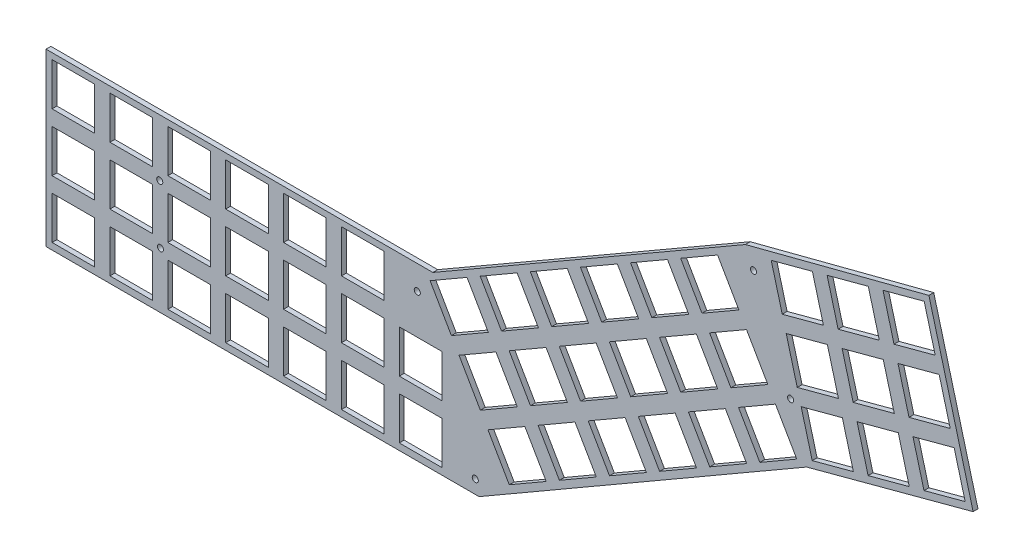
SolidWorks part; units mm, degrees
ref_plane "Plan de face" through (0, 0, 0) normal (0, 0, 1) x (1, 0, 0)
ref_plane "Plan de dessus" through (0, 0, 0) normal (0, 1, 0) x (1, 0, 0)
ref_plane "Plan de droite" through (0, 0, 0) normal (1, 0, 0) x (0, 0, -1)
sketch "Model" plane through (0, 0, 0) normal (0, 0, 1) x (1, 0, 0)
  line L0 (-149.6088, -15.6876) -> (-135.6088, -15.6876) construction
  line L1 (-149.6088, 3.3124) -> (-135.6088, 3.3124) construction
  line L2 (-149.6088, 3.3124) -> (-149.6088, -10.6876) construction
  line L3 (-149.6088, -10.6876) -> (-135.6088, -10.6876) construction
  line L4 (-135.6088, 3.3124) -> (-135.6088, -10.6876) construction
  line L5 (-149.6088, -15.6876) -> (-149.6088, -29.6876) construction
  line L6 (-149.6088, -29.6876) -> (-135.6088, -29.6876) construction
  line L7 (-135.6088, -15.6876) -> (-135.6088, -29.6876) construction
  line L8 (-149.6088, -34.6876) -> (-135.6088, -34.6876) construction
  line L9 (-149.6088, -34.6876) -> (-149.6088, -48.6876) construction
  line L10 (-149.6088, -48.6876) -> (-135.6088, -48.6876) construction
  line L11 (-135.6088, -34.6876) -> (-135.6088, -48.6876) construction
  line L12 (-149.6088, 3.3124) -> (-149.6088, -15.6876) construction
  line L13 (-130.6088, -15.6876) -> (-116.6088, -15.6876) construction
  line L14 (-130.6088, 3.3124) -> (-116.6088, 3.3124) construction
  line L15 (-130.6088, 3.3124) -> (-130.6088, -10.6876) construction
  line L16 (-130.6088, -10.6876) -> (-116.6088, -10.6876) construction
  line L17 (-116.6088, 3.3124) -> (-116.6088, -10.6876) construction
  line L18 (-130.6088, -15.6876) -> (-130.6088, -29.6876) construction
  line L19 (-130.6088, -29.6876) -> (-116.6088, -29.6876) construction
  line L20 (-116.6088, -15.6876) -> (-116.6088, -29.6876) construction
  line L21 (-130.6088, -34.6876) -> (-116.6088, -34.6876) construction
  line L22 (-130.6088, -34.6876) -> (-130.6088, -48.6876) construction
  line L23 (-130.6088, -48.6876) -> (-116.6088, -48.6876) construction
  line L24 (-116.6088, -34.6876) -> (-116.6088, -48.6876) construction
  line L25 (-130.6088, 3.3124) -> (-130.6088, -15.6876) construction
  line L26 (-111.6088, -15.6876) -> (-97.6088, -15.6876) construction
  line L27 (-111.6088, 3.3124) -> (-97.6088, 3.3124) construction
  line L28 (-111.6088, 3.3124) -> (-111.6088, -10.6876) construction
  line L29 (-111.6088, -10.6876) -> (-97.6088, -10.6876) construction
  line L30 (-97.6088, 3.3124) -> (-97.6088, -10.6876) construction
  line L31 (-111.6088, -15.6876) -> (-111.6088, -29.6876) construction
  line L32 (-111.6088, -29.6876) -> (-97.6088, -29.6876) construction
  line L33 (-97.6088, -15.6876) -> (-97.6088, -29.6876) construction
  line L34 (-111.6088, -34.6876) -> (-97.6088, -34.6876) construction
  line L35 (-111.6088, -34.6876) -> (-111.6088, -48.6876) construction
  line L36 (-111.6088, -48.6876) -> (-97.6088, -48.6876) construction
  line L37 (-97.6088, -34.6876) -> (-97.6088, -48.6876) construction
  line L38 (-111.6088, 3.3124) -> (-111.6088, -15.6876) construction
  line L39 (-92.6088, -15.6876) -> (-78.6088, -15.6876) construction
  line L40 (-92.6088, 3.3124) -> (-78.6088, 3.3124) construction
  line L41 (-92.6088, 3.3124) -> (-92.6088, -10.6876) construction
  line L42 (-92.6088, -10.6876) -> (-78.6088, -10.6876) construction
  line L43 (-78.6088, 3.3124) -> (-78.6088, -10.6876) construction
  line L44 (-92.6088, -15.6876) -> (-92.6088, -29.6876) construction
  line L45 (-92.6088, -29.6876) -> (-78.6088, -29.6876) construction
  line L46 (-78.6088, -15.6876) -> (-78.6088, -29.6876) construction
  line L47 (-92.6088, -34.6876) -> (-78.6088, -34.6876) construction
  line L48 (-92.6088, -34.6876) -> (-92.6088, -48.6876) construction
  line L49 (-92.6088, -48.6876) -> (-78.6088, -48.6876) construction
  line L50 (-78.6088, -34.6876) -> (-78.6088, -48.6876) construction
  line L51 (-92.6088, 3.3124) -> (-92.6088, -15.6876) construction
  line L52 (-73.6088, -15.6876) -> (-59.6088, -15.6876) construction
  line L53 (-73.6088, 3.3124) -> (-59.6088, 3.3124) construction
  line L54 (-73.6088, 3.3124) -> (-73.6088, -10.6876) construction
  line L55 (-73.6088, -10.6876) -> (-59.6088, -10.6876) construction
  line L56 (-59.6088, 3.3124) -> (-59.6088, -10.6876) construction
  line L57 (-73.6088, -15.6876) -> (-73.6088, -29.6876) construction
  line L58 (-73.6088, -29.6876) -> (-59.6088, -29.6876) construction
  line L59 (-59.6088, -15.6876) -> (-59.6088, -29.6876) construction
  line L60 (-73.6088, -34.6876) -> (-59.6088, -34.6876) construction
  line L61 (-73.6088, -34.6876) -> (-73.6088, -48.6876) construction
  line L62 (-73.6088, -48.6876) -> (-59.6088, -48.6876) construction
  line L63 (-59.6088, -34.6876) -> (-59.6088, -48.6876) construction
  line L64 (-73.6088, 3.3124) -> (-73.6088, -15.6876) construction
  line L65 (-54.6088, -15.6876) -> (-40.6088, -15.6876) construction
  line L66 (-54.6088, 3.3124) -> (-40.6088, 3.3124) construction
  line L67 (-54.6088, 3.3124) -> (-54.6088, -10.6876) construction
  line L68 (-54.6088, -10.6876) -> (-40.6088, -10.6876) construction
  line L69 (-40.6088, 3.3124) -> (-40.6088, -10.6876) construction
  line L70 (-54.6088, -15.6876) -> (-54.6088, -29.6876) construction
  line L71 (-54.6088, -29.6876) -> (-40.6088, -29.6876) construction
  line L72 (-40.6088, -15.6876) -> (-40.6088, -29.6876) construction
  line L73 (-54.6088, -34.6876) -> (-40.6088, -34.6876) construction
  line L74 (-54.6088, -34.6876) -> (-54.6088, -48.6876) construction
  line L75 (-54.6088, -48.6876) -> (-40.6088, -48.6876) construction
  line L76 (-40.6088, -34.6876) -> (-40.6088, -48.6876) construction
  line L77 (-54.6088, 3.3124) -> (-54.6088, -15.6876) construction
  line L78 (-35.6088, -15.6876) -> (-21.6088, -15.6876) construction
  line L79 (-35.6088, 3.3124) -> (-21.6088, 3.3124) construction
  line L80 (-35.6088, 3.3124) -> (-35.6088, -10.6876) construction
  line L81 (-35.6088, -10.6876) -> (-21.6088, -10.6876) construction
  line L82 (-21.6088, 3.3124) -> (-21.6088, -10.6876) construction
  line L83 (-35.6088, -15.6876) -> (-35.6088, -29.6876) construction
  line L84 (-35.6088, -29.6876) -> (-21.6088, -29.6876) construction
  line L85 (-21.6088, -15.6876) -> (-21.6088, -29.6876) construction
  line L86 (-35.6088, -34.6876) -> (-21.6088, -34.6876) construction
  line L87 (-35.6088, -34.6876) -> (-35.6088, -48.6876) construction
  line L88 (-35.6088, -48.6876) -> (-21.6088, -48.6876) construction
  line L89 (-21.6088, -34.6876) -> (-21.6088, -48.6876) construction
  line L90 (-35.6088, 3.3124) -> (-35.6088, -15.6876) construction
  line L91 (-149.6088, -15.6876) -> (-130.6088, -15.6876) construction
  line L92 (-19.6088, -13.6876) -> (-18.8669, -14.9725) construction
  line L93 (-37.6088, 5.3124) -> (-19.6088, 5.3124) construction
  line L94 (-19.6088, 5.3124) -> (-19.6088, -12.6876) construction
  line L95 (-37.6088, -12.6876) -> (-19.6088, -12.6876) construction
  line L96 (-37.6088, 5.3124) -> (-37.6088, -12.6876) construction
  line L97 (-56.6088, 5.3124) -> (-38.6088, 5.3124) construction
  line L98 (-38.6088, 5.3124) -> (-38.6088, -12.6876) construction
  line L99 (-56.6088, -12.6876) -> (-38.6088, -12.6876) construction
  line L100 (-56.6088, 5.3124) -> (-56.6088, -12.6876) construction
  line L101 (3.8161, 21.7392) -> (12.8161, 6.1508) construction
  line L102 (12.8161, 6.1508) -> (-2.7723, -2.8492) construction
  line L103 (-11.7723, 12.7392) -> (-2.7723, -2.8492) construction
  line L104 (3.8161, 21.7392) -> (-11.7723, 12.7392) construction
  line L105 (-12.6383, 12.2392) -> (-3.6383, -3.3492) construction
  line L106 (-3.6383, -3.3492) -> (-19.2268, -12.3492) construction
  line L107 (-28.2268, 3.2392) -> (-19.2268, -12.3492) construction
  line L108 (-12.6383, 12.2392) -> (-28.2268, 3.2392) construction
  line L109 (88.6341, 26.8303) -> (73.0456, 17.8303) construction
  line L110 (-13.3704, 9.5072) -> (-3.8704, -6.9473) construction
  line L111 (3.0841, 19.0072) -> (12.5841, 2.5527) construction
  line L112 (19.5386, 28.5072) -> (29.0386, 12.0527) construction
  line L113 (35.9931, 38.0072) -> (45.4931, 21.5527) construction
  line L114 (52.4475, 47.5072) -> (61.9475, 31.0527) construction
  line L115 (68.902, 57.0072) -> (78.402, 40.5527) construction
  line L116 (73.0456, 17.8303) -> (82.0456, 2.2418) construction
  line L117 (-6.4947, -30.4018) -> (0.5053, -42.5261) construction
  line L118 (12.6296, -35.5261) -> (0.5053, -42.5261) construction
  line L119 (5.6296, -23.4018) -> (12.6296, -35.5261) construction
  line L120 (5.6296, -23.4018) -> (-6.4947, -30.4018) construction
  line L121 (-15.9947, -13.9473) -> (-8.9947, -26.0717) construction
  line L122 (3.1296, -19.0717) -> (-8.9947, -26.0717) construction
  line L123 (-3.8704, -6.9473) -> (3.1296, -19.0717) construction
  line L124 (-25.4947, 2.5072) -> (-18.4947, -9.6172) construction
  line L125 (-6.3704, -2.6172) -> (-18.4947, -9.6172) construction
  line L126 (-13.3704, 9.5072) -> (-6.3704, -2.6172) construction
  line L127 (-13.3704, 9.5072) -> (-25.4947, 2.5072) construction
  line L128 (-3.8704, -6.9473) -> (-15.9947, -13.9473) construction
  line L129 (9.9597, -20.9018) -> (16.9597, -33.0261) construction
  line L130 (29.0841, -26.0261) -> (16.9597, -33.0261) construction
  line L131 (22.0841, -13.9018) -> (29.0841, -26.0261) construction
  line L132 (22.0841, -13.9018) -> (9.9597, -20.9018) construction
  line L133 (0.4597, -4.4473) -> (7.4597, -16.5717) construction
  line L134 (19.5841, -9.5717) -> (7.4597, -16.5717) construction
  line L135 (12.5841, 2.5527) -> (19.5841, -9.5717) construction
  line L136 (-9.0403, 12.0072) -> (-2.0403, -0.1172) construction
  line L137 (10.0841, 6.8828) -> (-2.0403, -0.1172) construction
  line L138 (3.0841, 19.0072) -> (10.0841, 6.8828) construction
  line L139 (3.0841, 19.0072) -> (-9.0403, 12.0072) construction
  line L140 (12.5841, 2.5527) -> (0.4597, -4.4473) construction
  line L141 (26.4142, -11.4018) -> (33.4142, -23.5261) construction
  line L142 (45.5386, -16.5261) -> (33.4142, -23.5261) construction
  line L143 (38.5386, -4.4018) -> (45.5386, -16.5261) construction
  line L144 (38.5386, -4.4018) -> (26.4142, -11.4018) construction
  line L145 (16.9142, 5.0527) -> (23.9142, -7.0717) construction
  line L146 (36.0386, -0.0717) -> (23.9142, -7.0717) construction
  line L147 (29.0386, 12.0527) -> (36.0386, -0.0717) construction
  line L148 (7.4142, 21.5072) -> (14.4142, 9.3828) construction
  line L149 (26.5386, 16.3828) -> (14.4142, 9.3828) construction
  line L150 (19.5386, 28.5072) -> (26.5386, 16.3828) construction
  line L151 (19.5386, 28.5072) -> (7.4142, 21.5072) construction
  line L152 (29.0386, 12.0527) -> (16.9142, 5.0527) construction
  line L153 (42.8687, -1.9018) -> (49.8687, -14.0261) construction
  line L154 (61.9931, -7.0261) -> (49.8687, -14.0261) construction
  line L155 (54.9931, 5.0982) -> (61.9931, -7.0261) construction
  line L156 (54.9931, 5.0982) -> (42.8687, -1.9018) construction
  line L157 (33.3687, 14.5527) -> (40.3687, 2.4283) construction
  line L158 (52.4931, 9.4283) -> (40.3687, 2.4283) construction
  line L159 (45.4931, 21.5527) -> (52.4931, 9.4283) construction
  line L160 (23.8687, 31.0072) -> (30.8687, 18.8828) construction
  line L161 (42.9931, 25.8828) -> (30.8687, 18.8828) construction
  line L162 (35.9931, 38.0072) -> (42.9931, 25.8828) construction
  line L163 (35.9931, 38.0072) -> (23.8687, 31.0072) construction
  line L164 (45.4931, 21.5527) -> (33.3687, 14.5527) construction
  line L165 (59.3232, 7.5982) -> (66.3232, -4.5261) construction
  line L166 (78.4475, 2.4739) -> (66.3232, -4.5261) construction
  line L167 (71.4475, 14.5982) -> (78.4475, 2.4739) construction
  line L168 (71.4475, 14.5982) -> (59.3232, 7.5982) construction
  line L169 (49.8232, 24.0527) -> (56.8232, 11.9283) construction
  line L170 (68.9475, 18.9283) -> (56.8232, 11.9283) construction
  line L171 (61.9475, 31.0527) -> (68.9475, 18.9283) construction
  line L172 (40.3232, 40.5072) -> (47.3232, 28.3828) construction
  line L173 (59.4475, 35.3828) -> (47.3232, 28.3828) construction
  line L174 (52.4475, 47.5072) -> (59.4475, 35.3828) construction
  line L175 (52.4475, 47.5072) -> (40.3232, 40.5072) construction
  line L176 (61.9475, 31.0527) -> (49.8232, 24.0527) construction
  line L177 (75.7777, 17.0982) -> (82.7777, 4.9739) construction
  line L178 (94.902, 11.9739) -> (82.7777, 4.9739) construction
  line L179 (87.902, 24.0982) -> (94.902, 11.9739) construction
  line L180 (87.902, 24.0982) -> (75.7777, 17.0982) construction
  line L181 (66.2777, 33.5527) -> (73.2777, 21.4283) construction
  line L182 (85.402, 28.4283) -> (73.2777, 21.4283) construction
  line L183 (78.402, 40.5527) -> (85.402, 28.4283) construction
  line L184 (56.7777, 50.0072) -> (63.7777, 37.8828) construction
  line L185 (75.902, 44.8828) -> (63.7777, 37.8828) construction
  line L186 (68.902, 57.0072) -> (75.902, 44.8828) construction
  line L187 (68.902, 57.0072) -> (56.7777, 50.0072) construction
  line L188 (78.402, 40.5527) -> (66.2777, 33.5527) construction
  line L189 (97.6341, 11.2418) -> (82.0456, 2.2418) construction
  line L190 (88.6341, 26.8303) -> (97.6341, 11.2418) construction
  line L191 (102.6968, 0.3259) -> (93.4333, 22.69) construction
  line L192 (93.8992, 29.0112) -> (98.558, 11.6245) construction
  line L193 (98.558, 11.6245) -> (115.9446, 16.2832) construction
  line L194 (111.2859, 33.6699) -> (115.9446, 16.2832) construction
  line L195 (86.5136, 64.3021) -> (91.4311, 45.9495) construction
  line L196 (93.8992, 29.0112) -> (111.2859, 33.6699) construction
  line L197 (91.4311, 45.9495) -> (104.9541, 49.573) construction
  line L198 (86.5136, 64.3021) -> (100.0365, 67.9256) construction
  line L199 (86.5136, 64.3021) -> (90.137, 50.7792) construction
  line L200 (90.137, 50.7792) -> (103.66, 54.4026) construction
  line L201 (100.0365, 67.9256) -> (103.66, 54.4026) construction
  line L202 (91.4311, 45.9495) -> (95.0546, 32.4266) construction
  line L203 (95.0546, 32.4266) -> (108.5776, 36.05) construction
  line L204 (104.9541, 49.573) -> (108.5776, 36.05) construction
  line L205 (96.3487, 27.5969) -> (109.8717, 31.2204) construction
  line L206 (96.3487, 27.5969) -> (99.9722, 14.074) construction
  line L207 (99.9722, 14.074) -> (113.4951, 17.6974) construction
  line L208 (109.8717, 31.2204) -> (113.4951, 17.6974) construction
  line L209 (109.7837, 50.8671) -> (123.3067, 54.4906) construction
  line L210 (104.8662, 69.2197) -> (118.3891, 72.8432) construction
  line L211 (104.8662, 69.2197) -> (108.4896, 55.6967) construction
  line L212 (108.4896, 55.6967) -> (122.0126, 59.3202) construction
  line L213 (118.3891, 72.8432) -> (122.0126, 59.3202) construction
  line L214 (109.7837, 50.8671) -> (113.4072, 37.3441) construction
  line L215 (113.4072, 37.3441) -> (126.9302, 40.9676) construction
  line L216 (123.3067, 54.4906) -> (126.9302, 40.9676) construction
  line L217 (114.7013, 32.5145) -> (128.2243, 36.138) construction
  line L218 (114.7013, 32.5145) -> (118.3248, 18.9915) construction
  line L219 (118.3248, 18.9915) -> (131.8477, 22.615) construction
  line L220 (128.2243, 36.138) -> (131.8477, 22.615) construction
  line L221 (112.2518, 33.9287) -> (116.9105, 16.5421) construction
  line L222 (116.9105, 16.5421) -> (134.2972, 21.2008) construction
  line L223 (129.6385, 38.5875) -> (134.2972, 21.2008) construction
  line L224 (104.8662, 69.2197) -> (109.7837, 50.8671) construction
  line L225 (112.2518, 33.9287) -> (129.6385, 38.5875) construction
  line L226 (128.1363, 55.7847) -> (141.6593, 59.4081) construction
  line L227 (123.2188, 74.1372) -> (136.7417, 77.7607) construction
  line L228 (123.2188, 74.1372) -> (126.8422, 60.6143) construction
  line L229 (126.8422, 60.6143) -> (140.3652, 64.2378) construction
  line L230 (136.7417, 77.7607) -> (140.3652, 64.2378) construction
  line L231 (128.1363, 55.7847) -> (131.7598, 42.2617) construction
  line L232 (131.7598, 42.2617) -> (145.2828, 45.8852) construction
  line L233 (141.6593, 59.4081) -> (145.2828, 45.8852) construction
  line L234 (133.0539, 37.4321) -> (146.5768, 41.0555) construction
  line L235 (133.0539, 37.4321) -> (136.6774, 23.9091) construction
  line L236 (136.6774, 23.9091) -> (150.2003, 27.5326) construction
  line L237 (146.5768, 41.0555) -> (150.2003, 27.5326) construction
  line L238 (130.6044, 38.8463) -> (135.2631, 21.4596) construction
  line L239 (135.2631, 21.4596) -> (152.6498, 26.1184) construction
  line L240 (147.9911, 43.505) -> (152.6498, 26.1184) construction
  line L241 (123.2188, 74.1372) -> (128.1363, 55.7847) construction
  line L242 (130.6044, 38.8463) -> (147.9911, 43.505) construction
  line L243 (91.4311, 45.9495) -> (109.7837, 50.8671) construction
  line L244 (-37.6088, -13.6876) -> (-19.6088, -13.6876) construction
  line L245 (-19.6088, -13.6876) -> (-19.6088, -31.6876) construction
  line L246 (-37.6088, -31.6876) -> (-19.6088, -31.6876) construction
  line L247 (-37.6088, -13.6876) -> (-37.6088, -31.6876) construction
  line L248 (-3.1383, -4.2153) -> (-18.7268, -13.2153) construction
  line L249 (-18.7268, -13.2153) -> (-9.7268, -28.8037) construction
  line L250 (5.8617, -19.8037) -> (-9.7268, -28.8037) construction
  line L251 (-3.1383, -4.2153) -> (5.8617, -19.8037) construction
  line L252 (-18.7268, -13.2153) -> (-18.009, -14.4585) construction
  line L253 (88.9817, 47.3637) -> (93.6404, 29.9771) construction
  line L254 (93.6404, 29.9771) -> (111.0271, 34.6358) construction
  line L255 (106.3683, 52.0225) -> (111.0271, 34.6358) construction
  line L256 (88.9817, 47.3637) -> (106.3683, 52.0225) construction
  line L257 (79.1341, 43.2847) -> (88.1341, 27.6963) construction
  line L258 (88.1341, 27.6963) -> (72.5456, 18.6963) construction
  line L259 (63.5456, 34.2847) -> (72.5456, 18.6963) construction
  line L260 (79.1341, 43.2847) -> (63.5456, 34.2847) construction
  line L261 (120.7693, 75.5515) -> (138.1559, 80.2102) construction
  line L262 (-170.3739, 2.0225) -> (-152.3739, 2.0225) construction
  line L263 (-170.3739, 2.0225) -> (-170.3739, -30.9775) construction
  line L264 (-170.3739, -30.9775) -> (-152.3739, -30.9775) construction
  line L265 (-152.3739, 2.0225) -> (-152.3739, -30.9775) construction
  line L266 (138.1559, 80.2102) -> (142.8147, 62.8235) construction
  line L267 (125.428, 58.1648) -> (142.8147, 62.8235) construction
  line L268 (120.7693, 75.5515) -> (125.428, 58.1648) construction
  line L269 (-151.6088, -50.6876) -> (-133.6088, -50.6876) construction
  line L270 (-133.6088, -32.6876) -> (-133.6088, -50.6876) construction
  line L271 (-151.6088, -32.6876) -> (-133.6088, -32.6876) construction
  line L272 (-151.6088, -32.6876) -> (-151.6088, -50.6876) construction
  line L273 (-37.6088, -50.6876) -> (-19.6088, -50.6876) construction
  line L274 (-19.6088, -32.6876) -> (-19.6088, -50.6876) construction
  line L275 (-37.6088, -32.6876) -> (-19.6088, -32.6876) construction
  line L276 (-37.6088, -32.6876) -> (-37.6088, -50.6876) construction
  line L277 (-151.6088, 5.3124) -> (-133.6088, 5.3124) construction
  line L278 (-133.6088, 5.3124) -> (-133.6088, -12.6876) construction
  line L279 (-151.6088, -12.6876) -> (-133.6088, -12.6876) construction
  line L280 (-151.6088, 5.3124) -> (-151.6088, -12.6876) construction
  line L281 (69.6341, 59.7392) -> (54.0456, 50.7392) construction
  line L282 (54.0456, 50.7392) -> (63.0456, 35.1508) construction
  line L283 (78.6341, 44.1508) -> (63.0456, 35.1508) construction
  line L284 (69.6341, 59.7392) -> (78.6341, 44.1508) construction
  line L285 (-172.3739, 5.3124) -> (-24.636, 5.3124)
  line L286 (-24.636, 5.3124) -> (77.9848, 64.5605)
  line L287 (138.1559, 80.2102) -> (77.9848, 64.5605)
  line L288 (138.1559, 80.2102) -> (152.6498, 26.1184)
  line L289 (152.6498, 26.1184) -> (98.065, 11.5079)
  line L290 (98.065, 11.5079) -> (82.0456, 2.2418)
  line L291 (82.0456, 2.2418) -> (-9.4597, -50.6876)
  line L292 (-37.6088, -50.6876) -> (-19.6088, -50.6876)
  line L293 (-19.6088, -50.6876) -> (-9.4597, -50.6876)
  line L294 (-172.3739, 5.3124) -> (-172.3739, -50.6876)
  line L295 (-172.3739, -50.6876) -> (-37.6088, -50.6876)
  line L296 (101.9307, 2.1754) -> (100.0173, 6.7948) construction
  line L297 (-152.3739, 2.0225) -> (-172.3739, 2.0225) construction
  line L298 (-152.3739, 5.3124) -> (-172.3739, 5.3124) construction
  line L299 (-152.3739, 5.3124) -> (-152.3739, -32.6876) construction
  line L300 (-152.3739, -32.6876) -> (-172.3739, -32.6876) construction
  line L301 (-172.3739, 5.3124) -> (-172.3739, -32.6876) construction
  circle A0 centre (100.0173, 6.7948) radius 1.5 construction
sketch "Esquisse2" plane through (0, 0, 0) normal (0, 0, 1) x (1, 0, 0)
  line L0 (152.8114, 25.9717) -> (138.2826, 80.2215)
  line L1 (98.1506, 11.3316) -> (152.8114, 25.9717)
  line L2 (-9.3986, -50.8585) -> (98.1506, 11.3316)
  line L3 (-151.6088, -50.8585) -> (-9.3986, -50.8585)
  line L5 (-24.5886, 5.3017) -> (-151.6088, 5.2929)
  line L6 (78.0109, 64.5416) -> (-24.5886, 5.3017)
  line L7 (138.2826, 80.2215) -> (78.0109, 64.5416)
  line L40 (-151.6088, 5.3124) -> (-151.6088, -50.8585)
  line L41 (-54.6088, -34.6876) -> (-54.6088, -48.6876) construction
  line L42 (-54.6088, -48.6876) -> (-40.6088, -48.6876) construction
  line L43 (-40.6088, -34.6876) -> (-40.6088, -48.6876) construction
  line L44 (-54.6088, -34.6876) -> (-40.6088, -34.6876) construction
  line L45 (-35.6088, -34.6876) -> (-35.6088, -48.6876) construction
  line L46 (-35.6088, -48.6876) -> (-21.6088, -48.6876) construction
  line L47 (-21.6088, -34.6876) -> (-21.6088, -48.6876) construction
  line L48 (-35.6088, -34.6876) -> (-21.6088, -34.6876) construction
  line L49 (-35.6088, -15.6876) -> (-35.6088, -29.6876) construction
  line L50 (-35.6088, -29.6876) -> (-21.6088, -29.6876) construction
  line L51 (-21.6088, -15.6876) -> (-21.6088, -29.6876) construction
  line L52 (-35.6088, -15.6876) -> (-21.6088, -15.6876) construction
  line L53 (-54.6088, -15.6876) -> (-54.6088, -29.6876) construction
  line L54 (-54.6088, -29.6876) -> (-40.6088, -29.6876) construction
  line L55 (-40.6088, -15.6876) -> (-40.6088, -29.6876) construction
  line L56 (-54.6088, -15.6876) -> (-40.6088, -15.6876) construction
  line L57 (-54.6088, 3.3124) -> (-54.6088, -10.6876) construction
  line L58 (-54.6088, -10.6876) -> (-40.6088, -10.6876) construction
  line L59 (-40.6088, 3.3124) -> (-40.6088, -10.6876) construction
  line L60 (-54.6088, 3.3124) -> (-40.6088, 3.3124) construction
  line L61 (-73.6088, -34.6876) -> (-73.6088, -48.6876) construction
  line L62 (-73.6088, -48.6876) -> (-59.6088, -48.6876) construction
  line L63 (-59.6088, -34.6876) -> (-59.6088, -48.6876) construction
  line L64 (-73.6088, -34.6876) -> (-59.6088, -34.6876) construction
  line L65 (-73.6088, -15.6876) -> (-73.6088, -29.6876) construction
  line L66 (-73.6088, -29.6876) -> (-59.6088, -29.6876) construction
  line L67 (-59.6088, -15.6876) -> (-59.6088, -29.6876) construction
  line L68 (-73.6088, -15.6876) -> (-59.6088, -15.6876) construction
  line L69 (-73.6088, 3.3124) -> (-73.6088, -10.6876) construction
  line L70 (-73.6088, -10.6876) -> (-59.6088, -10.6876) construction
  line L71 (-59.6088, 3.3124) -> (-59.6088, -10.6876) construction
  line L72 (-73.6088, 3.3124) -> (-59.6088, 3.3124) construction
  line L73 (-92.6088, -34.6876) -> (-92.6088, -48.6876) construction
  line L74 (-92.6088, -48.6876) -> (-78.6088, -48.6876) construction
  line L75 (-78.6088, -34.6876) -> (-78.6088, -48.6876) construction
  line L76 (-92.6088, -34.6876) -> (-78.6088, -34.6876) construction
  line L77 (-92.6088, -15.6876) -> (-92.6088, -29.6876) construction
  line L78 (-92.6088, -29.6876) -> (-78.6088, -29.6876) construction
  line L79 (-78.6088, -15.6876) -> (-78.6088, -29.6876) construction
  line L80 (-92.6088, -15.6876) -> (-78.6088, -15.6876) construction
  line L81 (-92.6088, 3.3124) -> (-92.6088, -10.6876) construction
  line L82 (-92.6088, -10.6876) -> (-78.6088, -10.6876) construction
  line L83 (-78.6088, 3.3124) -> (-78.6088, -10.6876) construction
  line L84 (-92.6088, 3.3124) -> (-78.6088, 3.3124) construction
  line L85 (-111.6088, -34.6876) -> (-111.6088, -48.6876) construction
  line L86 (-111.6088, -48.6876) -> (-97.6088, -48.6876) construction
  line L87 (-97.6088, -34.6876) -> (-97.6088, -48.6876) construction
  line L88 (-111.6088, -34.6876) -> (-97.6088, -34.6876) construction
  line L89 (-111.6088, -15.6876) -> (-111.6088, -29.6876) construction
  line L90 (-111.6088, -29.6876) -> (-97.6088, -29.6876) construction
  line L91 (-97.6088, -15.6876) -> (-97.6088, -29.6876) construction
  line L92 (-111.6088, -15.6876) -> (-97.6088, -15.6876) construction
  line L93 (-130.6088, -34.6876) -> (-130.6088, -48.6876) construction
  line L94 (-130.6088, -48.6876) -> (-116.6088, -48.6876) construction
  line L95 (-116.6088, -34.6876) -> (-116.6088, -48.6876) construction
  line L96 (-130.6088, -34.6876) -> (-116.6088, -34.6876) construction
  line L97 (-130.6088, -15.6876) -> (-130.6088, -29.6876) construction
  line L98 (-130.6088, -29.6876) -> (-116.6088, -29.6876) construction
  line L99 (-116.6088, -15.6876) -> (-116.6088, -29.6876) construction
  line L100 (-130.6088, -15.6876) -> (-116.6088, -15.6876) construction
  line L101 (-149.6088, -34.6876) -> (-149.6088, -48.6876) construction
  line L102 (-149.6088, -48.6876) -> (-135.6088, -48.6876) construction
  line L103 (-135.6088, -34.6876) -> (-135.6088, -48.6876) construction
  line L104 (-149.6088, -34.6876) -> (-135.6088, -34.6876) construction
  line L105 (-149.6088, -15.6876) -> (-149.6088, -29.6876) construction
  line L106 (-149.6088, -29.6876) -> (-135.6088, -29.6876) construction
  line L107 (-135.6088, -15.6876) -> (-135.6088, -29.6876) construction
  line L108 (-149.6088, -15.6876) -> (-135.6088, -15.6876) construction
  line L109 (-111.6088, 3.3124) -> (-111.6088, -10.6876) construction
  line L110 (-111.6088, -10.6876) -> (-97.6088, -10.6876) construction
  line L111 (-97.6088, 3.3124) -> (-97.6088, -10.6876) construction
  line L112 (-111.6088, 3.3124) -> (-97.6088, 3.3124) construction
  line L113 (-130.6088, 3.3124) -> (-130.6088, -10.6876) construction
  line L114 (-130.6088, -10.6876) -> (-116.6088, -10.6876) construction
  line L115 (-116.6088, 3.3124) -> (-116.6088, -10.6876) construction
  line L116 (-130.6088, 3.3124) -> (-116.6088, 3.3124) construction
  line L117 (-149.6088, 3.3124) -> (-149.6088, -10.6876) construction
  line L118 (-149.6088, -10.6876) -> (-135.6088, -10.6876) construction
  line L119 (-135.6088, 3.3124) -> (-135.6088, -10.6876) construction
  line L120 (-149.6088, 3.3124) -> (-135.6088, 3.3124) construction
  line L121 (-54.6088, -34.6876) -> (-54.6088, -48.6876)
  line L122 (-54.6088, -48.6876) -> (-40.6088, -48.6876)
  line L123 (-40.6088, -34.6876) -> (-40.6088, -48.6876)
  line L124 (-54.6088, -34.6876) -> (-40.6088, -34.6876)
  line L125 (-35.6088, -34.6876) -> (-35.6088, -48.6876)
  line L126 (-35.6088, -48.6876) -> (-21.6088, -48.6876)
  line L127 (-21.6088, -34.6876) -> (-21.6088, -48.6876)
  line L128 (-35.6088, -34.6876) -> (-21.6088, -34.6876)
  line L129 (-35.6088, -15.6876) -> (-35.6088, -29.6876)
  line L130 (-35.6088, -29.6876) -> (-21.6088, -29.6876)
  line L131 (-21.6088, -15.6876) -> (-21.6088, -29.6876)
  line L132 (-35.6088, -15.6876) -> (-21.6088, -15.6876)
  line L133 (-54.6088, -15.6876) -> (-54.6088, -29.6876)
  line L134 (-54.6088, -29.6876) -> (-40.6088, -29.6876)
  line L135 (-40.6088, -15.6876) -> (-40.6088, -29.6876)
  line L136 (-54.6088, -15.6876) -> (-40.6088, -15.6876)
  line L137 (-54.6088, 3.3124) -> (-54.6088, -10.6876)
  line L138 (-54.6088, -10.6876) -> (-40.6088, -10.6876)
  line L139 (-40.6088, 3.3124) -> (-40.6088, -10.6876)
  line L140 (-54.6088, 3.3124) -> (-40.6088, 3.3124)
  line L141 (-73.6088, -34.6876) -> (-73.6088, -48.6876)
  line L142 (-73.6088, -48.6876) -> (-59.6088, -48.6876)
  line L143 (-59.6088, -34.6876) -> (-59.6088, -48.6876)
  line L144 (-73.6088, -34.6876) -> (-59.6088, -34.6876)
  line L145 (-73.6088, -15.6876) -> (-73.6088, -29.6876)
  line L146 (-73.6088, -29.6876) -> (-59.6088, -29.6876)
  line L147 (-59.6088, -15.6876) -> (-59.6088, -29.6876)
  line L148 (-73.6088, -15.6876) -> (-59.6088, -15.6876)
  line L149 (-73.6088, 3.3124) -> (-73.6088, -10.6876)
  line L150 (-73.6088, -10.6876) -> (-59.6088, -10.6876)
  line L151 (-59.6088, 3.3124) -> (-59.6088, -10.6876)
  line L152 (-73.6088, 3.3124) -> (-59.6088, 3.3124)
  line L153 (-92.6088, -34.6876) -> (-92.6088, -48.6876)
  line L154 (-92.6088, -48.6876) -> (-78.6088, -48.6876)
  line L155 (-78.6088, -34.6876) -> (-78.6088, -48.6876)
  line L156 (-92.6088, -34.6876) -> (-78.6088, -34.6876)
  line L157 (-92.6088, -15.6876) -> (-92.6088, -29.6876)
  line L158 (-92.6088, -29.6876) -> (-78.6088, -29.6876)
  line L159 (-78.6088, -15.6876) -> (-78.6088, -29.6876)
  line L160 (-92.6088, -15.6876) -> (-78.6088, -15.6876)
  line L161 (-92.6088, 3.3124) -> (-92.6088, -10.6876)
  line L162 (-92.6088, -10.6876) -> (-78.6088, -10.6876)
  line L163 (-78.6088, 3.3124) -> (-78.6088, -10.6876)
  line L164 (-92.6088, 3.3124) -> (-78.6088, 3.3124)
  line L165 (-111.6088, -34.6876) -> (-111.6088, -48.6876)
  line L166 (-111.6088, -48.6876) -> (-97.6088, -48.6876)
  line L167 (-97.6088, -34.6876) -> (-97.6088, -48.6876)
  line L168 (-111.6088, -34.6876) -> (-97.6088, -34.6876)
  line L169 (-111.6088, -15.6876) -> (-111.6088, -29.6876)
  line L170 (-111.6088, -29.6876) -> (-97.6088, -29.6876)
  line L171 (-97.6088, -15.6876) -> (-97.6088, -29.6876)
  line L172 (-111.6088, -15.6876) -> (-97.6088, -15.6876)
  line L173 (-130.6088, -34.6876) -> (-130.6088, -48.6876)
  line L174 (-130.6088, -48.6876) -> (-116.6088, -48.6876)
  line L175 (-116.6088, -34.6876) -> (-116.6088, -48.6876)
  line L176 (-130.6088, -34.6876) -> (-116.6088, -34.6876)
  line L177 (-130.6088, -15.6876) -> (-130.6088, -29.6876)
  line L178 (-130.6088, -29.6876) -> (-116.6088, -29.6876)
  line L179 (-116.6088, -15.6876) -> (-116.6088, -29.6876)
  line L180 (-130.6088, -15.6876) -> (-116.6088, -15.6876)
  line L181 (-149.6088, -34.6876) -> (-149.6088, -48.6876)
  line L182 (-149.6088, -48.6876) -> (-135.6088, -48.6876)
  line L183 (-135.6088, -34.6876) -> (-135.6088, -48.6876)
  line L184 (-149.6088, -34.6876) -> (-135.6088, -34.6876)
  line L185 (-149.6088, -15.6876) -> (-149.6088, -29.6876)
  line L186 (-149.6088, -29.6876) -> (-135.6088, -29.6876)
  line L187 (-135.6088, -15.6876) -> (-135.6088, -29.6876)
  line L188 (-149.6088, -15.6876) -> (-135.6088, -15.6876)
  line L189 (-111.6088, 3.3124) -> (-111.6088, -10.6876)
  line L190 (-111.6088, -10.6876) -> (-97.6088, -10.6876)
  line L191 (-97.6088, 3.3124) -> (-97.6088, -10.6876)
  line L192 (-111.6088, 3.3124) -> (-97.6088, 3.3124)
  line L193 (-130.6088, 3.3124) -> (-130.6088, -10.6876)
  line L194 (-130.6088, -10.6876) -> (-116.6088, -10.6876)
  line L195 (-116.6088, 3.3124) -> (-116.6088, -10.6876)
  line L196 (-130.6088, 3.3124) -> (-116.6088, 3.3124)
  line L197 (-149.6088, 3.3124) -> (-149.6088, -10.6876)
  line L198 (-149.6088, -10.6876) -> (-135.6088, -10.6876)
  line L199 (-135.6088, 3.3124) -> (-135.6088, -10.6876)
  line L200 (-149.6088, 3.3124) -> (-135.6088, 3.3124)
  line L201 (96.3487, 27.5969) -> (99.9722, 14.074) construction
  line L202 (99.9722, 14.074) -> (113.4951, 17.6974) construction
  line L203 (109.8717, 31.2204) -> (113.4951, 17.6974) construction
  line L204 (96.3487, 27.5969) -> (109.8717, 31.2204) construction
  line L205 (91.4311, 45.9495) -> (95.0546, 32.4266) construction
  line L206 (95.0546, 32.4266) -> (108.5776, 36.05) construction
  line L207 (104.9541, 49.573) -> (108.5776, 36.05) construction
  line L208 (91.4311, 45.9495) -> (104.9541, 49.573) construction
  line L209 (109.7837, 50.8671) -> (113.4072, 37.3441) construction
  line L210 (113.4072, 37.3441) -> (126.9302, 40.9676) construction
  line L211 (123.3067, 54.4906) -> (126.9302, 40.9676) construction
  line L212 (109.7837, 50.8671) -> (123.3067, 54.4906) construction
  line L213 (114.7013, 32.5145) -> (118.3248, 18.9915) construction
  line L214 (118.3248, 18.9915) -> (131.8477, 22.615) construction
  line L215 (128.2243, 36.138) -> (131.8477, 22.615) construction
  line L216 (114.7013, 32.5145) -> (128.2243, 36.138) construction
  line L217 (133.0539, 37.4321) -> (136.6774, 23.9091) construction
  line L218 (136.6774, 23.9091) -> (150.2003, 27.5326) construction
  line L219 (146.5768, 41.0555) -> (150.2003, 27.5326) construction
  line L220 (133.0539, 37.4321) -> (146.5768, 41.0555) construction
  line L221 (128.1363, 55.7847) -> (131.7598, 42.2617) construction
  line L222 (131.7598, 42.2617) -> (145.2828, 45.8852) construction
  line L223 (141.6593, 59.4081) -> (145.2828, 45.8852) construction
  line L224 (128.1363, 55.7847) -> (141.6593, 59.4081) construction
  line L225 (123.2188, 74.1372) -> (126.8422, 60.6143) construction
  line L226 (126.8422, 60.6143) -> (140.3652, 64.2378) construction
  line L227 (136.7417, 77.7607) -> (140.3652, 64.2378) construction
  line L228 (123.2188, 74.1372) -> (136.7417, 77.7607) construction
  line L229 (104.8662, 69.2197) -> (108.4896, 55.6967) construction
  line L230 (108.4896, 55.6967) -> (122.0126, 59.3202) construction
  line L231 (118.3891, 72.8432) -> (122.0126, 59.3202) construction
  line L232 (104.8662, 69.2197) -> (118.3891, 72.8432) construction
  line L233 (86.5136, 64.3021) -> (90.137, 50.7792) construction
  line L234 (90.137, 50.7792) -> (103.66, 54.4026) construction
  line L235 (100.0365, 67.9256) -> (103.66, 54.4026) construction
  line L236 (86.5136, 64.3021) -> (100.0365, 67.9256) construction
  line L237 (87.902, 24.0982) -> (94.902, 11.9739) construction
  line L238 (94.902, 11.9739) -> (82.7777, 4.9739) construction
  line L239 (75.7777, 17.0982) -> (82.7777, 4.9739) construction
  line L240 (87.902, 24.0982) -> (75.7777, 17.0982) construction
  line L241 (78.402, 40.5527) -> (85.402, 28.4283) construction
  line L242 (85.402, 28.4283) -> (73.2777, 21.4283) construction
  line L243 (66.2777, 33.5527) -> (73.2777, 21.4283) construction
  line L244 (78.402, 40.5527) -> (66.2777, 33.5527) construction
  line L245 (68.902, 57.0072) -> (75.902, 44.8828) construction
  line L246 (75.902, 44.8828) -> (63.7777, 37.8828) construction
  line L247 (56.7777, 50.0072) -> (63.7777, 37.8828) construction
  line L248 (68.902, 57.0072) -> (56.7777, 50.0072) construction
  line L249 (71.4475, 14.5982) -> (78.4475, 2.4739) construction
  line L250 (78.4475, 2.4739) -> (66.3232, -4.5261) construction
  line L251 (59.3232, 7.5982) -> (66.3232, -4.5261) construction
  line L252 (71.4475, 14.5982) -> (59.3232, 7.5982) construction
  line L253 (61.9475, 31.0527) -> (68.9475, 18.9283) construction
  line L254 (68.9475, 18.9283) -> (56.8232, 11.9283) construction
  line L255 (49.8232, 24.0527) -> (56.8232, 11.9283) construction
  line L256 (61.9475, 31.0527) -> (49.8232, 24.0527) construction
  line L257 (52.4475, 47.5072) -> (59.4475, 35.3828) construction
  line L258 (59.4475, 35.3828) -> (47.3232, 28.3828) construction
  line L259 (40.3232, 40.5072) -> (47.3232, 28.3828) construction
  line L260 (52.4475, 47.5072) -> (40.3232, 40.5072) construction
  line L261 (54.9931, 5.0982) -> (61.9931, -7.0261) construction
  line L262 (61.9931, -7.0261) -> (49.8687, -14.0261) construction
  line L263 (42.8687, -1.9018) -> (49.8687, -14.0261) construction
  line L264 (54.9931, 5.0982) -> (42.8687, -1.9018) construction
  line L265 (45.4931, 21.5527) -> (52.4931, 9.4283) construction
  line L266 (52.4931, 9.4283) -> (40.3687, 2.4283) construction
  line L267 (33.3687, 14.5527) -> (40.3687, 2.4283) construction
  line L268 (45.4931, 21.5527) -> (33.3687, 14.5527) construction
  line L269 (38.5386, -4.4018) -> (45.5386, -16.5261) construction
  line L270 (45.5386, -16.5261) -> (33.4142, -23.5261) construction
  line L271 (26.4142, -11.4018) -> (33.4142, -23.5261) construction
  line L272 (38.5386, -4.4018) -> (26.4142, -11.4018) construction
  line L273 (29.0386, 12.0527) -> (36.0386, -0.0717) construction
  line L274 (36.0386, -0.0717) -> (23.9142, -7.0717) construction
  line L275 (16.9142, 5.0527) -> (23.9142, -7.0717) construction
  line L276 (29.0386, 12.0527) -> (16.9142, 5.0527) construction
  line L277 (35.9931, 38.0072) -> (42.9931, 25.8828) construction
  line L278 (42.9931, 25.8828) -> (30.8687, 18.8828) construction
  line L279 (23.8687, 31.0072) -> (30.8687, 18.8828) construction
  line L280 (35.9931, 38.0072) -> (23.8687, 31.0072) construction
  line L281 (19.5386, 28.5072) -> (26.5386, 16.3828) construction
  line L282 (26.5386, 16.3828) -> (14.4142, 9.3828) construction
  line L283 (7.4142, 21.5072) -> (14.4142, 9.3828) construction
  line L284 (19.5386, 28.5072) -> (7.4142, 21.5072) construction
  line L285 (3.0841, 19.0072) -> (10.0841, 6.8828) construction
  line L286 (10.0841, 6.8828) -> (-2.0403, -0.1172) construction
  line L287 (-9.0403, 12.0072) -> (-2.0403, -0.1172) construction
  line L288 (3.0841, 19.0072) -> (-9.0403, 12.0072) construction
  line L289 (12.5841, 2.5527) -> (19.5841, -9.5717) construction
  line L290 (19.5841, -9.5717) -> (7.4597, -16.5717) construction
  line L291 (0.4597, -4.4473) -> (7.4597, -16.5717) construction
  line L292 (12.5841, 2.5527) -> (0.4597, -4.4473) construction
  line L293 (22.0841, -13.9018) -> (29.0841, -26.0261) construction
  line L294 (29.0841, -26.0261) -> (16.9597, -33.0261) construction
  line L295 (9.9597, -20.9018) -> (16.9597, -33.0261) construction
  line L296 (22.0841, -13.9018) -> (9.9597, -20.9018) construction
  line L297 (5.6296, -23.4018) -> (12.6296, -35.5261) construction
  line L298 (12.6296, -35.5261) -> (0.5053, -42.5261) construction
  line L299 (-6.4947, -30.4018) -> (0.5053, -42.5261) construction
  line L300 (5.6296, -23.4018) -> (-6.4947, -30.4018) construction
  line L301 (-3.8704, -6.9473) -> (3.1296, -19.0717) construction
  line L302 (3.1296, -19.0717) -> (-8.9947, -26.0717) construction
  line L303 (-15.9947, -13.9473) -> (-8.9947, -26.0717) construction
  line L304 (-3.8704, -6.9473) -> (-15.9947, -13.9473) construction
  line L305 (-13.3704, 9.5072) -> (-25.4947, 2.5072) construction
  line L306 (-25.4947, 2.5072) -> (-18.4947, -9.6172) construction
  line L307 (-6.3704, -2.6172) -> (-18.4947, -9.6172) construction
  line L308 (-13.3704, 9.5072) -> (-6.3704, -2.6172) construction
  line L309 (96.3487, 27.5969) -> (99.9722, 14.074)
  line L310 (99.9722, 14.074) -> (113.4951, 17.6974)
  line L311 (109.8717, 31.2204) -> (113.4951, 17.6974)
  line L312 (96.3487, 27.5969) -> (109.8717, 31.2204)
  line L313 (91.4311, 45.9495) -> (95.0546, 32.4266)
  line L314 (95.0546, 32.4266) -> (108.5776, 36.05)
  line L315 (104.9541, 49.573) -> (108.5776, 36.05)
  line L316 (91.4311, 45.9495) -> (104.9541, 49.573)
  line L317 (109.7837, 50.8671) -> (113.4072, 37.3441)
  line L318 (113.4072, 37.3441) -> (126.9302, 40.9676)
  line L319 (123.3067, 54.4906) -> (126.9302, 40.9676)
  line L320 (109.7837, 50.8671) -> (123.3067, 54.4906)
  line L321 (114.7013, 32.5145) -> (118.3248, 18.9915)
  line L322 (118.3248, 18.9915) -> (131.8477, 22.615)
  line L323 (128.2243, 36.138) -> (131.8477, 22.615)
  line L324 (114.7013, 32.5145) -> (128.2243, 36.138)
  line L325 (133.0539, 37.4321) -> (136.6774, 23.9091)
  line L326 (136.6774, 23.9091) -> (150.2003, 27.5326)
  line L327 (146.5768, 41.0555) -> (150.2003, 27.5326)
  line L328 (133.0539, 37.4321) -> (146.5768, 41.0555)
  line L329 (128.1363, 55.7847) -> (131.7598, 42.2617)
  line L330 (131.7598, 42.2617) -> (145.2828, 45.8852)
  line L331 (141.6593, 59.4081) -> (145.2828, 45.8852)
  line L332 (128.1363, 55.7847) -> (141.6593, 59.4081)
  line L333 (123.2188, 74.1372) -> (126.8422, 60.6143)
  line L334 (126.8422, 60.6143) -> (140.3652, 64.2378)
  line L335 (136.7417, 77.7607) -> (140.3652, 64.2378)
  line L336 (123.2188, 74.1372) -> (136.7417, 77.7607)
  line L337 (104.8662, 69.2197) -> (108.4896, 55.6967)
  line L338 (108.4896, 55.6967) -> (122.0126, 59.3202)
  line L339 (118.3891, 72.8432) -> (122.0126, 59.3202)
  line L340 (104.8662, 69.2197) -> (118.3891, 72.8432)
  line L341 (86.5136, 64.3021) -> (90.137, 50.7792)
  line L342 (90.137, 50.7792) -> (103.66, 54.4026)
  line L343 (100.0365, 67.9256) -> (103.66, 54.4026)
  line L344 (86.5136, 64.3021) -> (100.0365, 67.9256)
  line L345 (87.902, 24.0982) -> (94.902, 11.9739)
  line L346 (94.902, 11.9739) -> (82.7777, 4.9739)
  line L347 (75.7777, 17.0982) -> (82.7777, 4.9739)
  line L348 (87.902, 24.0982) -> (75.7777, 17.0982)
  line L349 (78.402, 40.5527) -> (85.402, 28.4283)
  line L350 (85.402, 28.4283) -> (73.2777, 21.4283)
  line L351 (66.2777, 33.5527) -> (73.2777, 21.4283)
  line L352 (78.402, 40.5527) -> (66.2777, 33.5527)
  line L353 (68.902, 57.0072) -> (75.902, 44.8828)
  line L354 (75.902, 44.8828) -> (63.7777, 37.8828)
  line L355 (56.7777, 50.0072) -> (63.7777, 37.8828)
  line L356 (68.902, 57.0072) -> (56.7777, 50.0072)
  line L357 (71.4475, 14.5982) -> (78.4475, 2.4739)
  line L358 (78.4475, 2.4739) -> (66.3232, -4.5261)
  line L359 (59.3232, 7.5982) -> (66.3232, -4.5261)
  line L360 (71.4475, 14.5982) -> (59.3232, 7.5982)
  line L361 (61.9475, 31.0527) -> (68.9475, 18.9283)
  line L362 (68.9475, 18.9283) -> (56.8232, 11.9283)
  line L363 (49.8232, 24.0527) -> (56.8232, 11.9283)
  line L364 (61.9475, 31.0527) -> (49.8232, 24.0527)
  line L365 (52.4475, 47.5072) -> (59.4475, 35.3828)
  line L366 (59.4475, 35.3828) -> (47.3232, 28.3828)
  line L367 (40.3232, 40.5072) -> (47.3232, 28.3828)
  line L368 (52.4475, 47.5072) -> (40.3232, 40.5072)
  line L369 (54.9931, 5.0982) -> (61.9931, -7.0261)
  line L370 (61.9931, -7.0261) -> (49.8687, -14.0261)
  line L371 (42.8687, -1.9018) -> (49.8687, -14.0261)
  line L372 (54.9931, 5.0982) -> (42.8687, -1.9018)
  line L373 (45.4931, 21.5527) -> (52.4931, 9.4283)
  line L374 (52.4931, 9.4283) -> (40.3687, 2.4283)
  line L375 (33.3687, 14.5527) -> (40.3687, 2.4283)
  line L376 (45.4931, 21.5527) -> (33.3687, 14.5527)
  line L377 (38.5386, -4.4018) -> (45.5386, -16.5261)
  line L378 (45.5386, -16.5261) -> (33.4142, -23.5261)
  line L379 (26.4142, -11.4018) -> (33.4142, -23.5261)
  line L380 (38.5386, -4.4018) -> (26.4142, -11.4018)
  line L381 (29.0386, 12.0527) -> (36.0386, -0.0717)
  line L382 (36.0386, -0.0717) -> (23.9142, -7.0717)
  line L383 (16.9142, 5.0527) -> (23.9142, -7.0717)
  line L384 (29.0386, 12.0527) -> (16.9142, 5.0527)
  line L385 (35.9931, 38.0072) -> (42.9931, 25.8828)
  line L386 (42.9931, 25.8828) -> (30.8687, 18.8828)
  line L387 (23.8687, 31.0072) -> (30.8687, 18.8828)
  line L388 (35.9931, 38.0072) -> (23.8687, 31.0072)
  line L389 (19.5386, 28.5072) -> (26.5386, 16.3828)
  line L390 (26.5386, 16.3828) -> (14.4142, 9.3828)
  line L391 (7.4142, 21.5072) -> (14.4142, 9.3828)
  line L392 (19.5386, 28.5072) -> (7.4142, 21.5072)
  line L393 (3.0841, 19.0072) -> (10.0841, 6.8828)
  line L394 (10.0841, 6.8828) -> (-2.0403, -0.1172)
  line L395 (-9.0403, 12.0072) -> (-2.0403, -0.1172)
  line L396 (3.0841, 19.0072) -> (-9.0403, 12.0072)
  line L397 (12.5841, 2.5527) -> (19.5841, -9.5717)
  line L398 (19.5841, -9.5717) -> (7.4597, -16.5717)
  line L399 (0.4597, -4.4473) -> (7.4597, -16.5717)
  line L400 (12.5841, 2.5527) -> (0.4597, -4.4473)
  line L401 (22.0841, -13.9018) -> (29.0841, -26.0261)
  line L402 (29.0841, -26.0261) -> (16.9597, -33.0261)
  line L403 (9.9597, -20.9018) -> (16.9597, -33.0261)
  line L404 (22.0841, -13.9018) -> (9.9597, -20.9018)
  line L405 (5.6296, -23.4018) -> (12.6296, -35.5261)
  line L406 (12.6296, -35.5261) -> (0.5053, -42.5261)
  line L407 (-6.4947, -30.4018) -> (0.5053, -42.5261)
  line L408 (5.6296, -23.4018) -> (-6.4947, -30.4018)
  line L409 (-3.8704, -6.9473) -> (3.1296, -19.0717)
  line L410 (3.1296, -19.0717) -> (-8.9947, -26.0717)
  line L411 (-15.9947, -13.9473) -> (-8.9947, -26.0717)
  line L412 (-3.8704, -6.9473) -> (-15.9947, -13.9473)
  line L413 (-13.3704, 9.5072) -> (-25.4947, 2.5072)
  line L414 (-25.4947, 2.5072) -> (-18.4947, -9.6172)
  line L415 (-6.3704, -2.6172) -> (-18.4947, -9.6172)
  line L416 (-13.3704, 9.5072) -> (-6.3704, -2.6172)
  circle A0 centre (80.6856, 58.4893) radius 1
  circle A1 centre (92.8776, 28.0855) radius 1
  circle A2 centre (-29.7028, -2.6485) radius 1
  circle A4 centre (-10.6528, -46.4381) radius 1
  circle A5 centre (-114.2594, -13.4181) radius 1
  circle A6 centre (-114.0308, -32.4935) radius 1
  dimension "D1" = 2
  dimension "D2" = 2
  dimension "D3" = 2
extrude "Boss.-Extru.1" add sketch "Esquisse2" along normal blind 1.6 contours L5 L40 L3 L2 L1 L0 L7 L6 A6 A5 A4 A2 A1 A0 L412 L409 L410 L411 L408 L405 L406 L407 L404 L401 L402 L403 L400 L397 L398 L399 L396 L393 L394 L395 L392 L389 L390 L391
